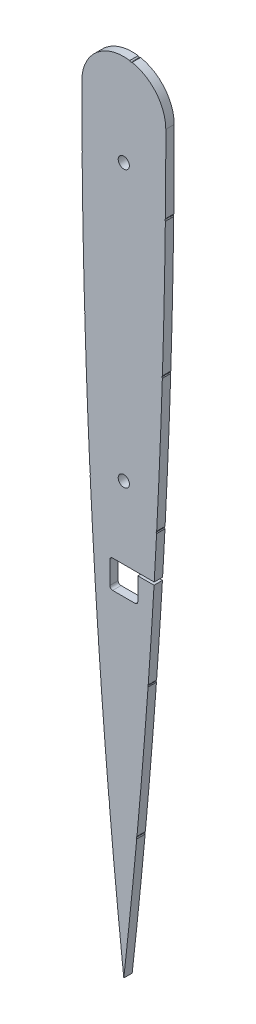
SolidWorks part; units mm, degrees
ref_plane "Front" through (0, 0, 0) normal (0, 0, 1) x (1, 0, 0)
ref_plane "Top" through (0, 0, 0) normal (0, 1, 0) x (1, 0, 0)
ref_plane "Right" through (0, 0, 0) normal (1, 0, 0) x (0, 0, -1)
sketch "Sketch2" plane through (0, 0, 0) normal (0, 0, 1) x (1, 0, 0)
  line L4 (-5, -143.1053) -> (-5, -151.1053)
  line L5 (-4, -152.1053) -> (4, -152.1053)
  line L6 (5, -151.1053) -> (5, -143.1053)
  line L7 (4, -142.1053) -> (-4, -142.1053)
  line L8 (-5, -143.1053) -> (-5, -151.1053)
  line L9 (-4, -152.1053) -> (4, -152.1053)
  line L10 (5, -151.1053) -> (5, -143.1053)
  line L11 (4, -142.1053) -> (-4, -142.1053)
  arc A0 (0, -270) -> (15, 0) centre (-2422.5, 0) ccw construction
  arc A1 (0, -270) -> (15, 0) centre (-2422.5, 0) ccw
  arc A2 (-15, 0) -> (0, -270) centre (2422.5, 0) ccw construction
  arc A3 (15, 0) -> (-15, 0) centre (0, 0) ccw construction
  arc A4 (-15, 0) -> (0, -270) centre (2422.5, 0) ccw
  arc A5 (15, 0) -> (-15, 0) centre (0, 0) ccw
  arc A10 (-4, -142.1053) -> (-5, -143.1053) centre (-4, -143.1053) ccw
  arc A11 (-5, -151.1053) -> (-4, -152.1053) centre (-4, -151.1053) ccw
  arc A12 (4, -152.1053) -> (5, -151.1053) centre (4, -151.1053) ccw
  arc A13 (5, -143.1053) -> (4, -142.1053) centre (4, -143.1053) ccw
  arc A14 (-4, -142.1053) -> (-5, -143.1053) centre (-4, -143.1053) ccw
  arc A15 (-5, -151.1053) -> (-4, -152.1053) centre (-4, -151.1053) ccw
  arc A16 (4, -152.1053) -> (5, -151.1053) centre (4, -151.1053) ccw
  arc A17 (5, -143.1053) -> (4, -142.1053) centre (4, -143.1053) ccw
  dimension "D1" = 0
extrude "Boss-Extrude1" add sketch "Sketch2" along normal blind 3
sketch "Sketch5" plane through (0, 0, 3) normal (0, 0, 1) x (1, 0, 0)
  text T0 " . . . . . . . . . . . ." font "Century Gothic" height in points 28
extrude "Cut-Extrude2" cut sketch "Sketch5" against normal blind 10
sketch "Sketch3" plane through (0, 0, 3) normal (0, 0, 1) x (1, 0, 0)
  line L1 (0.0917, -143.1053) -> (26.6382, -143.1053)
  line L2 (0.0917, -143.1053) -> (0.0917, -142.1053)
  line L3 (0.0917, -142.1053) -> (26.6382, -142.1053)
  line L4 (26.6382, -143.1053) -> (26.6382, -142.1053)
  line L5 (4, -142.1053) -> (-4, -142.1053) construction
  line L6 (-4, -152.1053) -> (4, -152.1053) construction
  circle A0 centre (0, -17.7949) radius 2
  circle A1 centre (0, -116.2734) radius 2
  point P17 (0, -152.1053)
  dimension "D2" = 4
  dimension "D1" = 1
extrude "Cut-Extrude1" cut sketch "Sketch3" against normal blind 10
sketch "Sketch6" plane through (0, 0, 3) normal (0, 0, 1) x (1, 0, 0)
  line L0 (-4, -152.1053) -> (4, -152.1053) construction
  line L1 (25, 22.6881) -> (-25, 22.6881)
  line L2 (25, 22.6881) -> (25, -280)
  line L3 (25, -280) -> (-25, -280)
  line L4 (-25, 22.6881) -> (-25, -280)
  point P6 (0, -152.1053)
  point P7 (0, -280)
  point P9 (25, 22.6881)
  dimension "D1" = 50
  dimension "D2" = 10
